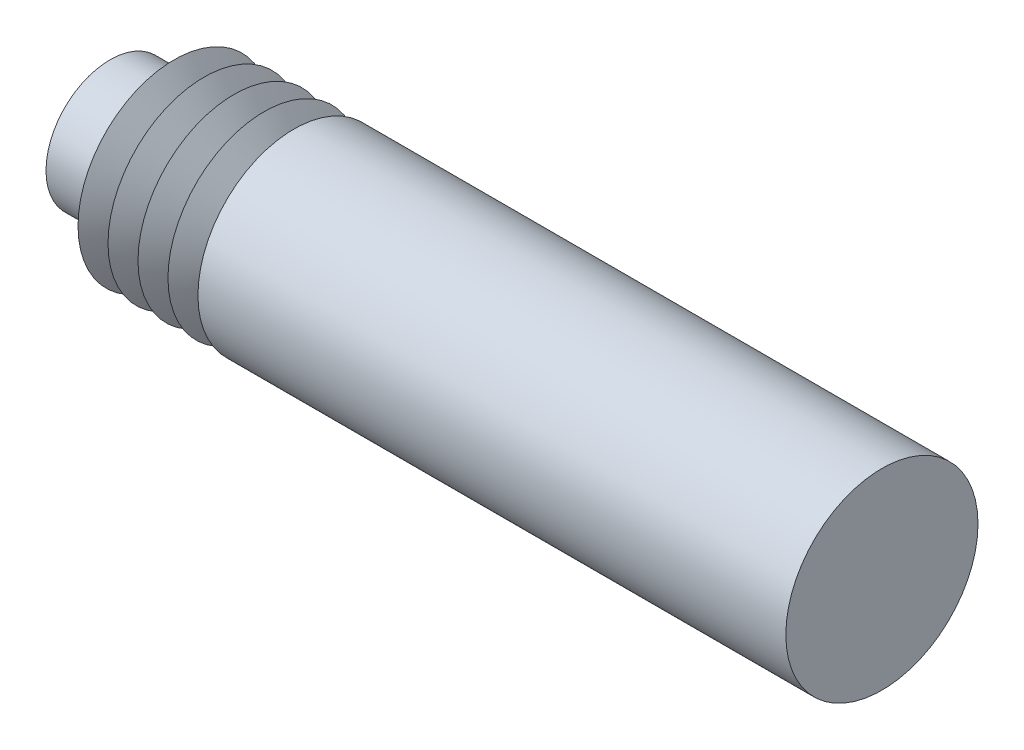
SolidWorks part; units mm, degrees
ref_plane "Plano frontal" through (0, 0, 0) normal (0, 0, 1) x (1, 0, 0)
ref_plane "Plano superior" through (0, 0, 0) normal (0, 1, 0) x (1, 0, 0)
ref_plane "Plano direito" through (0, 0, 0) normal (1, 0, 0) x (0, 0, -1)
sketch "Esboço1" plane through (0, 0, 0) normal (0, 0, 1) x (1, 0, 0)
  line L0 (-15.245, 0) -> (-15.245, 2.5)
  line L1 (-30.125, 2.5) -> (-30.125, 5)
  line L2 (30.125, 7.5) -> (30.125, 0)
  line L3 (-30.125, 5) -> (-25.125, 5)
  line L4 (-25.125, 5) -> (-25.125, 7.5)
  line L5 (-15.765, 7.5) -> (30.125, 7.5)
  line L6 (0, 0) -> (62.7162, 0) construction
  line L7 (30.125, 0) -> (-15.245, 0)
  line L8 (-15.245, 2.5) -> (-30.125, 2.5)
  line L10 (-22.785, 7.5) -> (-21.615, 5.7)
  line L11 (-25.125, 7.5) -> (-23.955, 5.7)
  line L12 (-23.955, 5.7) -> (-22.785, 7.5)
  line L13 (-21.615, 5.7) -> (-20.445, 7.5)
  line L14 (-20.445, 7.5) -> (-19.275, 5.7)
  line L15 (-19.275, 5.7) -> (-18.105, 7.5)
  line L16 (-18.105, 7.5) -> (-16.935, 5.7)
  line L17 (-16.935, 5.7) -> (-15.765, 7.5)
  point P4 (0, 0)
  point P6 (0, 0)
  dimension "D1" = 2.5
  dimension "D2" = 2.5
  dimension "D3" = 7.5
  dimension "D4" = 5
  dimension "D5" = 14.88
  dimension "D6" = 60.25
  dimension "D7" = 2.34
  dimension "D8" = 1.17
  dimension "D9" = 1.8
  dimension "D10" = 45.89
  dimension "D11" = 1.17
  dimension "D12" = 2.34
  dimension "D13" = 1.17
  dimension "D14" = 1.17
  dimension "D15" = 1.17
  dimension "D16" = 30.125
  dimension "D17" = 45.37
  dimension "D18" = 7.5
revolve "Revolução1" add sketch "Esboço1" angle 360 about L6
